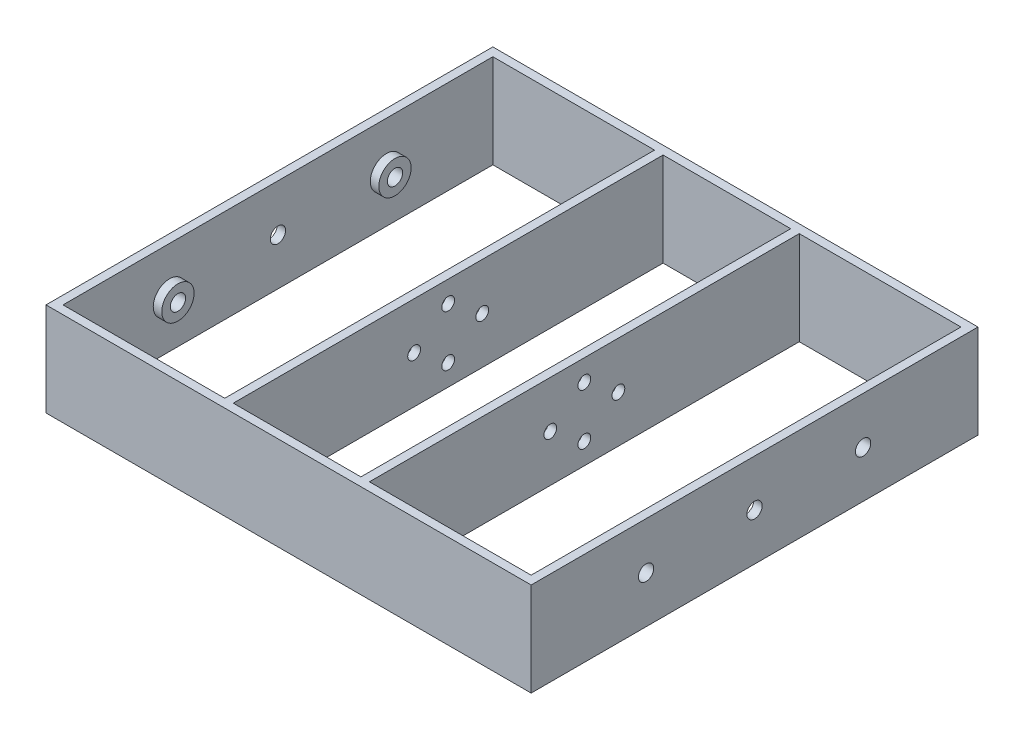
SolidWorks part; units mm, degrees
ref_plane "Front Plane" through (0, 0, 0) normal (0, 0, 1) x (1, 0, 0)
ref_plane "Top Plane" through (0, 0, 0) normal (0, 1, 0) x (1, 0, 0)
ref_plane "Right Plane" through (0, 0, 0) normal (1, 0, 0) x (0, 0, -1)
sketch "Sketch2" plane through (0, 0, 0) normal (1, 0, 0) x (0, 0, -1)
  line L0 (-25.5, 0) -> (25.5, 0) construction
  line L2 (52.5, 11) -> (-52.5, 11)
  line L3 (52.5, 11) -> (52.5, -11)
  line L4 (52.5, -11) -> (-52.5, -11)
  line L5 (-52.5, 11) -> (-52.5, -11)
  line L6 (52.5, 11) -> (-52.5, -11) construction
  line L7 (52.5, -11) -> (-52.5, 11) construction
  circle A0 centre (0, 0) radius 1.8
  circle A1 centre (-25.5, 0) radius 1.8
  circle A2 centre (25.5, 0) radius 1.8
  dimension "D1" = 25.5
  dimension "D2" = 3.6
  dimension "D3" = 105
  dimension "D4" = 22
extrude "Boss-Extrude1" add sketch "Sketch2" along normal blind 2 from offset 55
sketch "Sketch3" plane through (55, 0, 0) normal (-1, 0, 0) x (0, 0, 1)
  circle A0 centre (25.5, 0) radius 1.8 construction
  circle A2 centre (-25.5, 0) radius 1.8 construction
  circle A3 centre (25.5, 0) radius 1.8
  circle A5 centre (-25.5, 0) radius 1.8
  circle A6 centre (-25.5, 0) radius 3.8
  circle A8 centre (25.5, 0) radius 3.8
  dimension "D1" = 2
extrude "Boss-Extrude2" add sketch "Sketch3" along normal blind 2
sketch "Sketch5" plane through (0, 0, 0) normal (1, 0, 0) x (0, 0, -1)
  line L0 (8, 0) -> (-8, 0) construction
  line L1 (0, 6) -> (0, -6) construction
  line L3 (52.5, -11) -> (-52.5, -11)
  line L4 (52.5, -11) -> (52.5, 11)
  line L5 (52.5, 11) -> (-52.5, 11)
  line L6 (-52.5, -11) -> (-52.5, 11)
  line L7 (52.5, -11) -> (-52.5, 11) construction
  line L8 (52.5, 11) -> (-52.5, -11) construction
  circle A0 centre (8, 0) radius 1.5
  circle A1 centre (-8, 0) radius 1.5
  circle A2 centre (0, 6) radius 1.5
  circle A3 centre (0, -6) radius 1.5
  point P8 (0, 0)
  dimension "D1" = 16
  dimension "D3" = 3
  dimension "D2" = 12
extrude "Boss-Extrude3" add sketch "Sketch5" along normal blind 2 from offset 15 separate body
mirror "Mirror2" about plane through (0, 0, 0) normal (1, 0, 0) of bodies 106 109 101
sketch "Sketch6" plane through (0, 0, 0) normal (0, 1, 0) x (1, 0, 0)
  line L0 (57, 52.5) -> (57, -52.5) construction
  line L1 (-57, -52.5) -> (57, -52.5)
  line L2 (-57, -52.5) -> (-57, -50.5)
  line L3 (-57, -50.5) -> (57, -50.5)
  line L4 (57, -52.5) -> (57, -50.5)
  line L6 (-57, 52.5) -> (57, 52.5)
  line L7 (-57, 52.5) -> (-57, 50.5)
  line L8 (-57, 50.5) -> (57, 50.5)
  line L9 (57, 52.5) -> (57, 50.5)
  dimension "D1" = 2
extrude "Boss-Extrude4" add sketch "Sketch6" along normal mid plane 22
